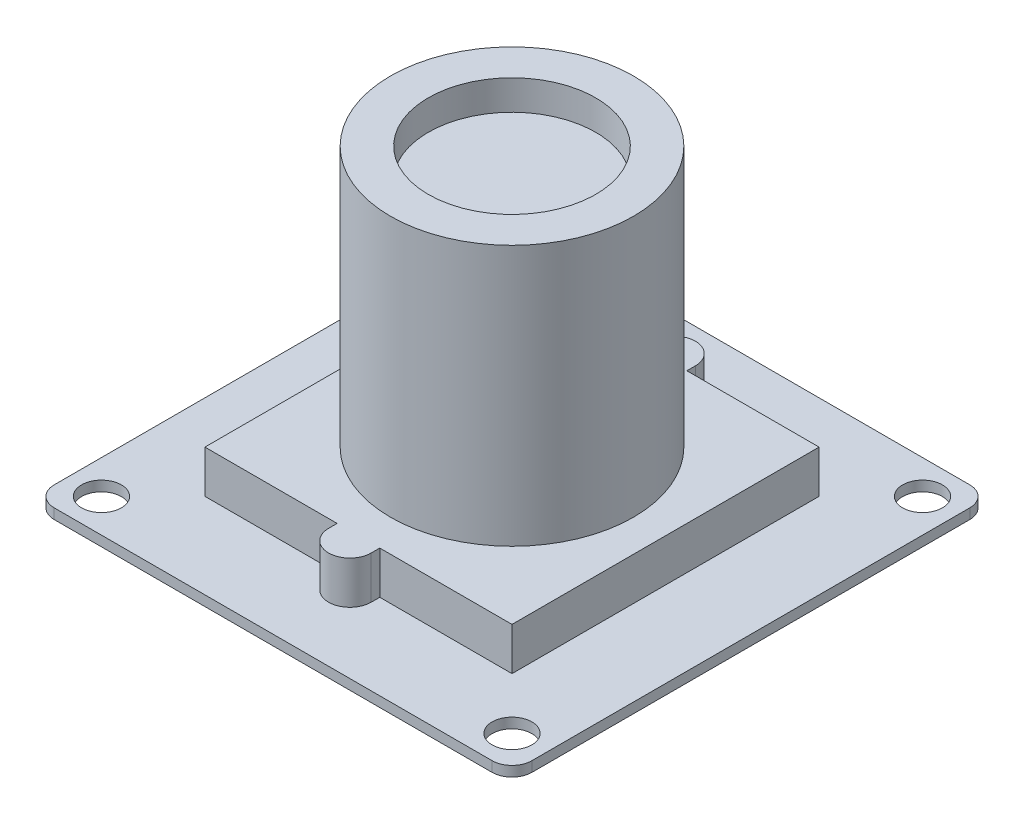
SolidWorks part; units mm, degrees
ref_plane "Front Plane" through (0, 0, 0) normal (0, 0, 1) x (1, 0, 0)
ref_plane "Top Plane" through (0, 0, 0) normal (0, 1, 0) x (1, 0, 0)
ref_plane "Right Plane" through (0, 0, 0) normal (1, 0, 0) x (0, 0, -1)
sketch "Sketch1" plane through (0, 0, 0) normal (0, 1, 0) x (1, 0, 0)
  line L1 (-16, -16) -> (16, -16)
  line L2 (-16, -16) -> (-16, 16)
  line L3 (-16, 16) -> (16, 16)
  line L4 (16, -16) -> (16, 16)
  line L5 (-16, -16) -> (16, 16) construction
  line L6 (-16, 16) -> (16, -16) construction
  point P0 (0, 0)
  dimension "D1" = 32
  dimension "D2" = 32
extrude "Boss-Extrude1" add sketch "Sketch1" along normal blind 0.681
sketch "Sketch2" plane through (0, 0.681, 0) normal (0, 1, 0) x (1, 0, 0)
  line L0 (16, 16) -> (16, 13.75) construction
  line L1 (16, -16) -> (16, 16) construction
  line L2 (16, 13.75) -> (13.75, 13.75) construction
  line L3 (-16, 16) -> (-16, 13.75) construction
  line L4 (-16, 16) -> (-16, -16) construction
  line L5 (16, -16) -> (13.75, -16) construction
  line L6 (-16, -16) -> (16, -16) construction
  line L7 (13.75, -16) -> (13.75, -13.75) construction
  line L8 (-16, -16) -> (-16, -13.75) construction
  line L9 (-16, -13.75) -> (-13.75, -13.75) construction
  line L10 (-16, 13.75) -> (-13.75, 13.75) construction
  circle A0 centre (13.75, 13.75) radius 1.3335
  circle A1 centre (-13.75, 13.75) radius 1.3335
  circle A2 centre (-13.75, -13.75) radius 1.3335
  circle A3 centre (13.75, -13.75) radius 1.3335
  dimension "D3" = 2.667
  dimension "D6" = 2.667
  dimension "D7" = 2.667
  dimension "D8" = 2.667
  dimension "D1" = 2.25
  dimension "D2" = 2.25
  dimension "D4" = 2.25
  dimension "D5" = 2.25
extrude "Cut-Extrude1" cut sketch "Sketch2" against normal blind 1
fillet "Fillet1" radius 1.335 4 edges at (16, 0.3405, -16) (16, 0.3405, 16) (-16, 0.3405, 16) (-16, 0.3405, -16)
sketch "Sketch3" plane through (0, 0.681, 0) normal (0, 1, 0) x (1, 0, 0)
  line L0 (0, 16) -> (0, 10.857) construction
  line L1 (-10.285, -10.285) -> (10.285, -10.285)
  line L2 (-10.285, -10.285) -> (-10.285, 10.285)
  line L3 (-10.285, 10.285) -> (10.285, 10.285)
  line L4 (10.285, -10.285) -> (10.285, 10.285)
  line L5 (-10.285, -10.285) -> (10.285, 10.285) construction
  line L6 (-10.285, 10.285) -> (10.285, -10.285) construction
  line L8 (14.665, 16) -> (-14.665, 16) construction
  line L9 (0, 10.857) -> (1.4285, 10.857) construction
  line L10 (0, 10.857) -> (-1.4285, 10.857) construction
  line L11 (1.4285, 10.857) -> (1.4285, 10.285)
  line L12 (-1.4285, 10.857) -> (-1.4285, 10.285)
  line L13 (0, -16) -> (0, -10.857) construction
  line L14 (-14.665, -16) -> (14.665, -16) construction
  line L15 (0, -10.857) -> (-1.4285, -10.857) construction
  line L16 (0, -10.857) -> (1.4285, -10.857) construction
  line L17 (-1.4285, -10.857) -> (-1.4285, -10.285)
  line L18 (1.4285, -10.857) -> (1.4285, -10.285)
  circle A0 centre (0, 10.857) radius 1.4285
  circle A1 centre (0, -10.857) radius 1.4285
  point P0 (0, 0)
  dimension "D3" = 5.143
  dimension "D4" = 2.857
  dimension "D1" = 20.57
  dimension "D2" = 20.57
  dimension "D5" = 5.143
extrude "Boss-Extrude2" add sketch "Sketch3" along normal blind 2.857 contours A1 L1 L4 L3 A0 L2 | L1 A1 | A1 L1 | A1 L18 L1 | A1 L1 L17 | L3 A0 | L3 A0 | A0 L3 L11 | A0 L12 L3
sketch "Sketch4" plane through (0, 3.538, 0) normal (0, 1, 0) x (1, 0, 0)
  circle A0 centre (0, 0) radius 8.1405
  dimension "D1" = 16.281
extrude "Boss-Extrude3" add sketch "Sketch4" along normal blind 17.46
sketch "Sketch6" plane through (0, 20.998, 0) normal (0, 1, 0) x (1, 0, 0)
  circle A0 centre (0, 0) radius 5.6075
  dimension "D1" = 11.215
extrude "Cut-Extrude2" cut sketch "Sketch6" against normal blind 2 contours A0
